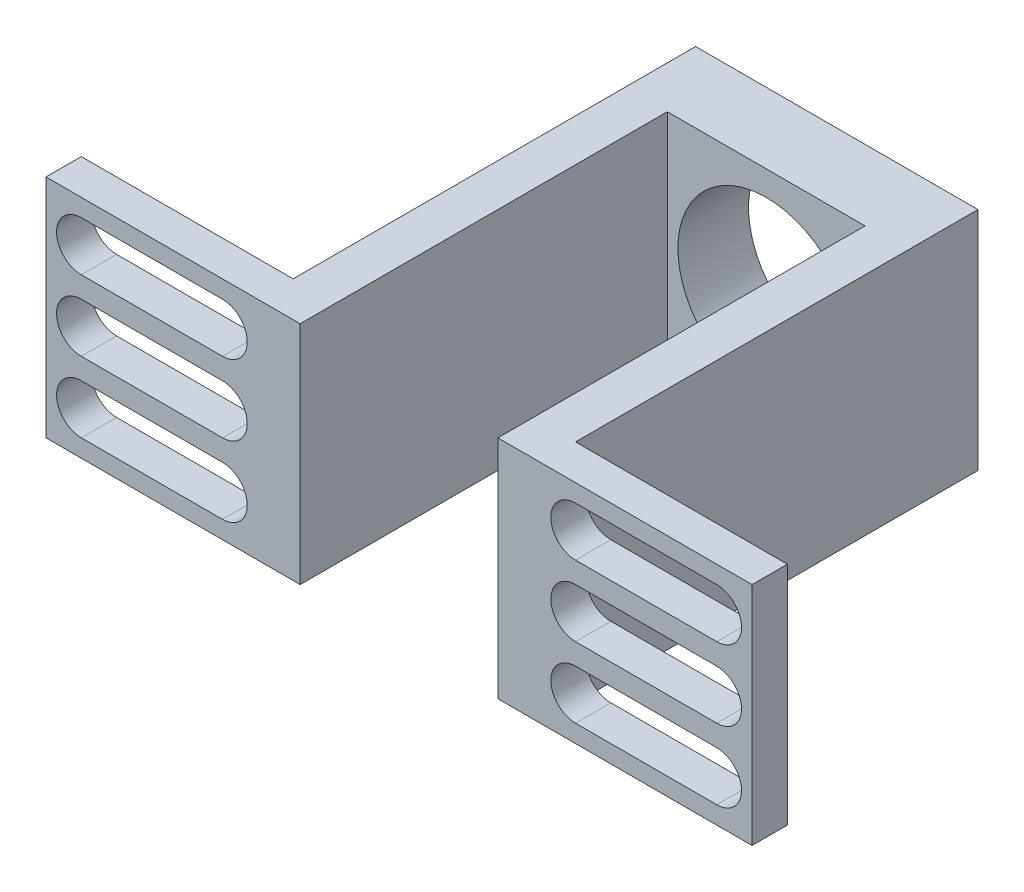
SolidWorks part; units mm, degrees
ref_plane "Front Plane" through (0, 0, 0) normal (0, 0, 1) x (1, 0, 0)
ref_plane "Top Plane" through (0, 0, 0) normal (0, 1, 0) x (1, 0, 0)
ref_plane "Right Plane" through (0, 0, 0) normal (1, 0, 0) x (0, 0, -1)
sketch "Sketch1" plane through (0, 0, 0) normal (0, 0, 1) x (1, 0, 0)
  line L1 (10, -8) -> (-10, -8)
  line L2 (10, -8) -> (10, 8)
  line L3 (10, 8) -> (-10, 8)
  line L4 (-10, -8) -> (-10, 8)
  line L5 (10, -8) -> (-10, 8) construction
  line L6 (10, 8) -> (-10, -8) construction
  circle A0 centre (0, 0) radius 6.25
  dimension "D1" = 12.5
  dimension "D2" = 20
  dimension "D3" = 16
extrude "Boss-Extrude1" add sketch "Sketch1" along normal blind 5
sketch "Sketch2" plane through (0, 0, 5) normal (0, 0, 1) x (1, 0, 0)
  line L0 (-10, -8) -> (10, -8) construction
  line L1 (-10, 8) -> (-7, 8)
  line L2 (-10, 8) -> (-10, -8)
  line L3 (-10, -8) -> (-7, -8)
  line L4 (-7, 8) -> (-7, -8)
  line L5 (0, -8) -> (0, 8) construction
  line L6 (10, 8) -> (-10, 8) construction
  line L7 (7, 8) -> (7, -8)
  line L8 (10, -8) -> (7, -8)
  line L9 (10, 8) -> (10, -8)
  line L10 (10, 8) -> (7, 8)
  dimension "D1" = 7
extrude "Boss-Extrude2" add sketch "Sketch2" along normal blind 26
sketch "Sketch3" plane through (0, 0, 31) normal (0, 0, 1) x (1, 0, 0)
  line L0 (-7, 8) -> (-10, 8) construction
  line L1 (-7, -8) -> (-25, -8)
  line L2 (-7, -8) -> (-7, 8)
  line L3 (-7, 8) -> (-25, 8)
  line L4 (-25, -8) -> (-25, 8)
  line L5 (-10, 8) -> (-10, -8) construction
  line L6 (0, 8) -> (0, -8) construction
  line L7 (7, 8) -> (-7, 8) construction
  line L8 (-7, -8) -> (7, -8) construction
  line L9 (25, -8) -> (25, 8)
  line L10 (7, 8) -> (25, 8)
  line L11 (7, -8) -> (7, 8)
  line L12 (7, -8) -> (25, -8)
  dimension "D1" = 0
  dimension "D2" = 15
extrude "Boss-Extrude3" add sketch "Sketch3" against normal blind 2.5
sketch "Sketch4" plane through (0, 0, 28.5) normal (0, 0, -1) x (-1, 0, 0)
  line L0 (-25, -5) -> (-10, -5) construction
  line L3 (0, -8) -> (0, 8) construction
  line L4 (10, -8) -> (-10, -8) construction
  line L5 (-10, 8) -> (10, 8) construction
  line L6 (-22.5, -5) -> (-12.5, -5) construction
  line L7 (-22.5, -3.25) -> (-12.5, -3.25)
  line L8 (-22.5, -6.75) -> (-12.5, -6.75)
  line L9 (25, 0) -> (10, 0) construction
  line L10 (25, -5) -> (10, -5) construction
  line L11 (22.5, 5) -> (12.5, 5) construction
  line L12 (22.5, 6.75) -> (12.5, 6.75)
  line L13 (-10, -8) -> (-10, 8) construction
  line L14 (-25, -8) -> (-25, 8) construction
  line L15 (-10, -8) -> (-25, -8) construction
  line L16 (-25, 0) -> (-10, 0) construction
  line L17 (-10, -8) -> (-10, 8) construction
  line L18 (-22.5, 0) -> (-12.5, 0) construction
  line L19 (-22.5, 1.75) -> (-12.5, 1.75)
  line L20 (-22.5, -1.75) -> (-12.5, -1.75)
  line L21 (-22.5, 5) -> (-12.5, 5) construction
  line L22 (-22.5, 6.75) -> (-12.5, 6.75)
  line L23 (-22.5, 3.25) -> (-12.5, 3.25)
  line L24 (22.5, 3.25) -> (12.5, 3.25)
  line L25 (22.5, 0) -> (12.5, 0) construction
  line L26 (22.5, 1.75) -> (12.5, 1.75)
  line L27 (22.5, -1.75) -> (12.5, -1.75)
  line L28 (22.5, -5) -> (12.5, -5) construction
  line L29 (22.5, -3.25) -> (12.5, -3.25)
  line L30 (22.5, -6.75) -> (12.5, -6.75)
  arc A0 (-22.5, -3.25) -> (-22.5, -6.75) centre (-22.5, -5) ccw
  arc A1 (-12.5, -6.75) -> (-12.5, -3.25) centre (-12.5, -5) ccw
  arc A2 (22.5, 6.75) -> (22.5, 3.25) centre (22.5, 5) cw
  arc A3 (12.5, 3.25) -> (12.5, 6.75) centre (12.5, 5) cw
  arc A4 (-22.5, 1.75) -> (-22.5, -1.75) centre (-22.5, 0) ccw
  arc A5 (-12.5, -1.75) -> (-12.5, 1.75) centre (-12.5, 0) ccw
  arc A6 (-22.5, 6.75) -> (-22.5, 3.25) centre (-22.5, 5) ccw
  arc A7 (-12.5, 3.25) -> (-12.5, 6.75) centre (-12.5, 5) ccw
  arc A8 (22.5, 1.75) -> (22.5, -1.75) centre (22.5, 0) cw
  arc A9 (12.5, -1.75) -> (12.5, 1.75) centre (12.5, 0) cw
  arc A10 (22.5, -3.25) -> (22.5, -6.75) centre (22.5, -5) cw
  arc A11 (12.5, -6.75) -> (12.5, -3.25) centre (12.5, -5) cw
  point P14 (-17.5, -5)
  point P25 (17.5, 5)
  point P28 (-17.5, -8)
  point P39 (-17.5, 0)
  point P46 (-17.5, 5)
  point P53 (17.5, 0)
  point P60 (17.5, -5)
  dimension "D1" = 1.75
  dimension "D8" = 2.5
  dimension "D2" = 10
  dimension "D3" = 0
  dimension "D4" = 0
  dimension "D5" = 3
  dimension "D7" = 10
  dimension "D6" = 3
extrude "Cut-Extrude1" cut sketch "Sketch4" against normal through all
